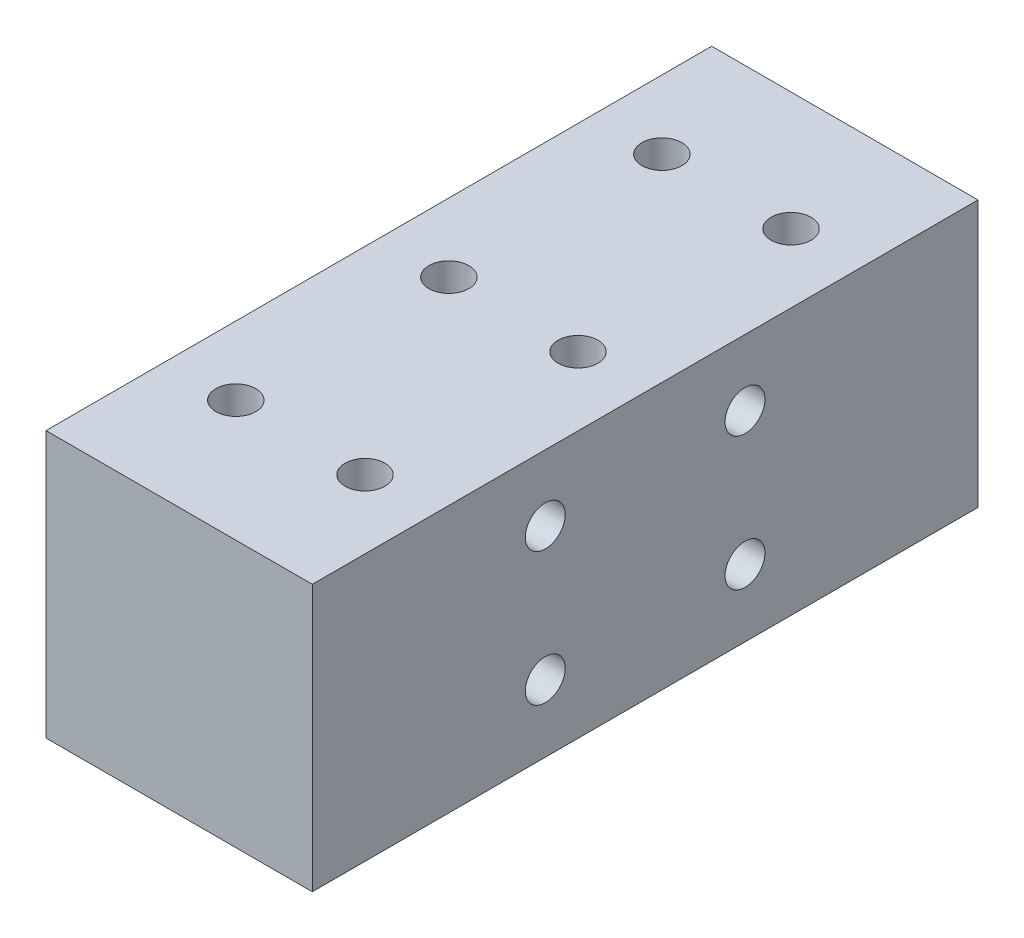
SolidWorks part; units mm, degrees
ref_plane "前视基准面" through (0, 0, 0) normal (0, 0, 1) x (1, 0, 0)
ref_plane "上视基准面" through (0, 0, 0) normal (0, 1, 0) x (1, 0, 0)
ref_plane "右视基准面" through (0, 0, 0) normal (1, 0, 0) x (0, 0, -1)
other "Configuration Table"
sketch "草图1" plane through (0, 0, 0) normal (0, 0, 1) x (1, 0, 0)
  line L5 (-8, -8) -> (8, 8) construction
  line L6 (-8, 8) -> (8, -8) construction
  line L7 (-10, -10) -> (10, -10)
  line L8 (-10, -10) -> (-10, 10)
  line L9 (-10, 10) -> (10, 10)
  line L10 (10, -10) -> (10, 10)
  line L11 (-10, -10) -> (10, 10) construction
  line L12 (-10, 10) -> (10, -10) construction
  point P0 (0, 0)
  point P6 (0, 0)
  dimension "D1" = 20
  dimension "D2" = 20
extrude "凸台-拉伸1" add sketch "草图1" along normal blind 50
sketch "草图2" plane through (10, 0, 0) normal (1, 0, 0) x (0, 0, -1)
  line L0 (-25, 10) -> (-25, -10) construction
  line L1 (-50, 10) -> (0, 10) construction
  line L2 (-50, -10) -> (0, -10) construction
  circle A0 centre (-32.5, 5.05) radius 1.5
  circle A1 centre (-17.5, 5.05) radius 1.5
  circle A2 centre (-32.5, -4.95) radius 1.5
  circle A3 centre (-17.5, -4.95) radius 1.5
  dimension "D1" = 10
  dimension "D2" = 15
  dimension "D4" = 3
  dimension "D3" = 4.95
extrude "切除-拉伸1" cut sketch "草图2" against normal up to surface (20 mm away) up to face at (-10, 0, 25)
sketch "草图4" plane through (0, -10, 0) normal (0, -1, 0) x (1, 0, 0)
  line L0 (0, 0) -> (0, 50) construction
  line L1 (-10, 50) -> (10, 50) construction
  circle A0 centre (-4.85, 40.893) radius 1.5
  circle A1 centre (-4.85, 24.893) radius 1.5
  circle A2 centre (-4.85, 8.893) radius 1.5
  circle A3 centre (4.85, 8.893) radius 1.5
  circle A4 centre (4.85, 24.893) radius 1.5
  circle A5 centre (4.85, 40.893) radius 1.5
  dimension "D1" = 3
extrude "切除-拉伸3" cut sketch "草图4" against normal up to surface (20 mm away) up to face at (0, 10, 25)
